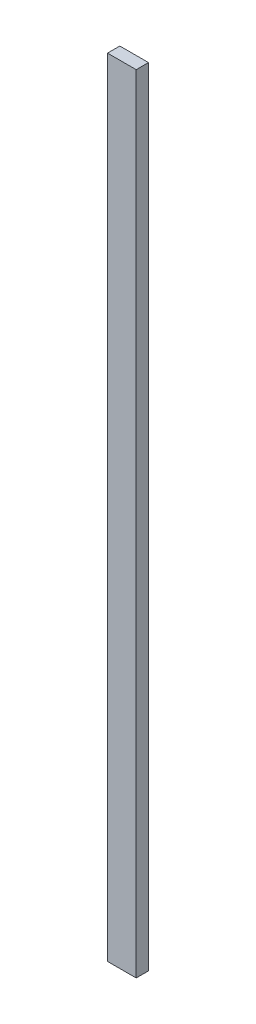
SolidWorks part; units mm, degrees
material "Pine"
ref_plane "Front Plane" through (0, 0, 0) normal (0, 0, 1) x (1, 0, 0)
ref_plane "Top Plane" through (0, 0, 0) normal (0, 1, 0) x (1, 0, 0)
ref_plane "Right Plane" through (0, 0, 0) normal (1, 0, 0) x (0, 0, -1)
sketch "Sketch1" plane through (0, 0, 0) normal (0, 1, 0) x (1, 0, 0)
  line L1 (-44.45, -19.05) -> (44.45, -19.05)
  line L2 (-44.45, -19.05) -> (-44.45, 19.05)
  line L3 (-44.45, 19.05) -> (44.45, 19.05)
  line L4 (44.45, -19.05) -> (44.45, 19.05)
  line L5 (-44.45, -19.05) -> (44.45, 19.05) construction
  line L6 (-44.45, 19.05) -> (44.45, -19.05) construction
  point P0 (0, 0)
  dimension "D1" = 88.9
  dimension "D2" = 38.1
extrude "Boss-Extrude1" add sketch "Sketch1" along normal blind 2438.4
